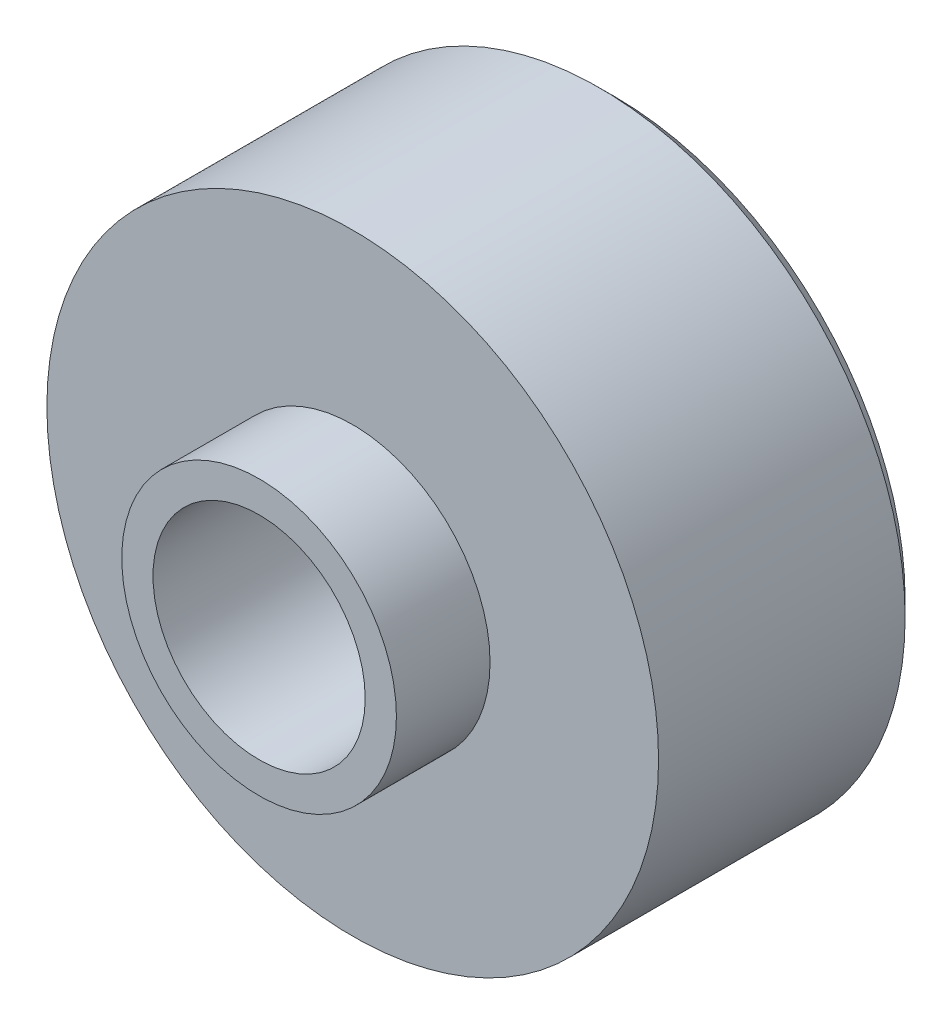
SolidWorks part; units mm, degrees
ref_plane "Front Plane" through (0, 0, 0) normal (0, 0, 1) x (1, 0, 0)
ref_plane "Top Plane" through (0, 0, 0) normal (0, 1, 0) x (1, 0, 0)
ref_plane "Right Plane" through (0, 0, 0) normal (1, 0, 0) x (0, 0, -1)
sketch "Sketch1" plane through (0, 0, 0) normal (0, 0, 1) x (1, 0, 0)
  circle A0 centre (0, 0) radius 1.7
  circle A2 centre (0, 0) radius 4.9
  dimension "D1" = 3.4
  dimension "D2" = 9.8
extrude "Boss-Extrude1" add sketch "Sketch1" along normal blind 4.2
sketch "Sketch2" plane through (0, 0, 4.2) normal (0, 0, 1) x (1, 0, 0)
  circle A0 centre (0, 0) radius 1.7
  circle A2 centre (0, 0) radius 2.2
  dimension "D1" = 3.4
  dimension "D2" = 0.5
extrude "Boss-Extrude2" add sketch "Sketch2" along normal blind 1.5
sketch "Sketch3" plane through (0, 0, 0) normal (0, 0, 1) x (1, 0, 0)
  circle A0 centre (0, 0) radius 2.2
  circle A1 centre (0, 0) radius 1.7
  dimension "D1" = 4.4
  dimension "D2" = 3.4
chamfer "Chamfer1" distance 0.25 angle 45 2 edges at (1.7, 0, 0) (4.9, 0, 0)
